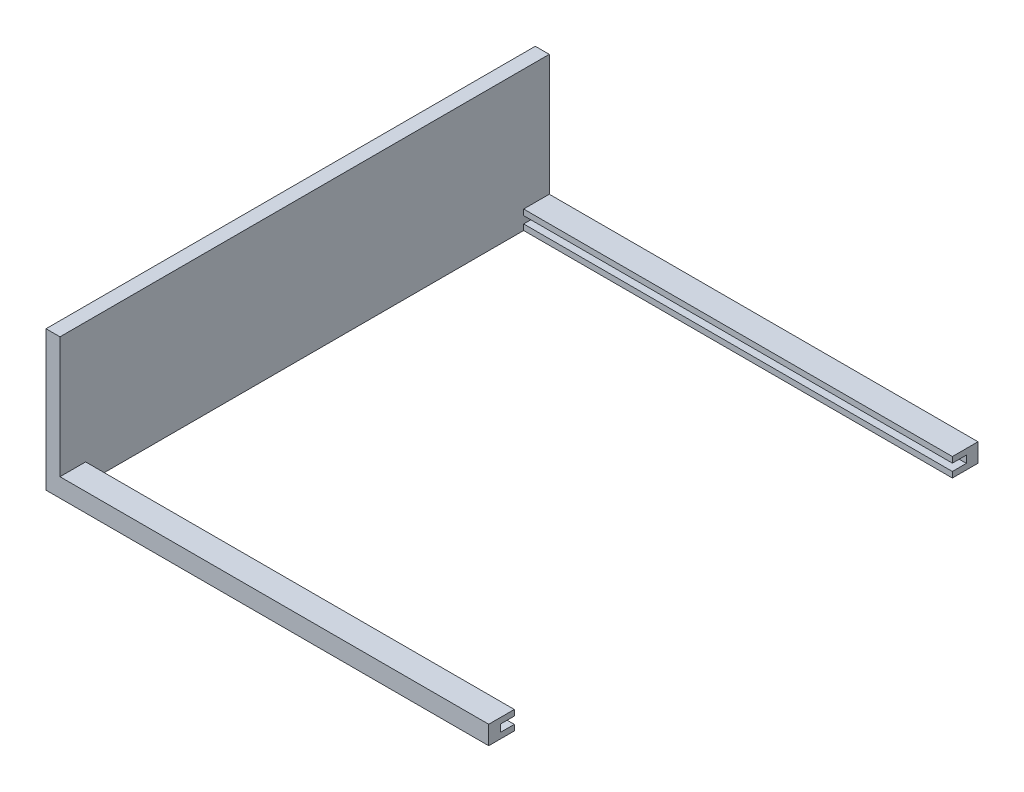
SolidWorks part; units mm, degrees
ref_plane "Front Plane" through (0, 0, 0) normal (0, 0, 1) x (1, 0, 0)
ref_plane "Top Plane" through (0, 0, 0) normal (0, 1, 0) x (1, 0, 0)
ref_plane "Right Plane" through (0, 0, 0) normal (1, 0, 0) x (0, 0, -1)
sketch "Sketch1" plane through (0, 0, 0) normal (0, 0, 1) x (1, 0, 0)
  line L0 (0, 26) -> (0, 0)
  line L1 (0, 26) -> (-3, 26)
  line L2 (-3, 26) -> (-3, -4)
  line L3 (-3, -4) -> (92, -4)
  line L4 (92, -4) -> (92, 0)
  line L5 (92, 0) -> (0, 0)
  dimension "D1" = 95
  dimension "D2" = 4
  dimension "D3" = 3
  dimension "D4" = 30
extrude "Boss-Extrude1" add sketch "Sketch1" against normal blind 105
sketch "Sketch2" plane through (0, 0, 0) normal (1, 0, 0) x (0, 0, -1)
  line L1 (99.5, -1.23) -> (102.5, -1.23)
  line L2 (102.5, -1.23) -> (102.5, -2.77)
  line L6 (5.5, 0) -> (5.5, -1.23)
  line L7 (102.5, -2.77) -> (99.5, -2.77)
  line L8 (105, 0) -> (0, 0) construction
  line L9 (99.5, -1.23) -> (99.5, 0)
  line L15 (105, 0) -> (0, 0) construction
  line L16 (105, -4) -> (0, -4) construction
  line L17 (5.5, -4) -> (99.5, -4)
  line L18 (99.5, -4) -> (99.5, -2.77)
  line L19 (99.5, 0) -> (5.5, 0)
  line L20 (0, -4) -> (0, 0) construction
  line L21 (5.5, -1.23) -> (2.5, -1.23)
  line L22 (2.5, -1.23) -> (2.5, -2.77)
  line L23 (2.5, -2.77) -> (5.5, -2.77)
  line L24 (5.5, -2.77) -> (5.5, -4)
  line L25 (52.5, 26) -> (52.5, 16.3677) construction
  line L26 (105, 26) -> (0, 26) construction
  dimension "D1" = 94
  dimension "D2" = 5.5
  dimension "D3" = 3
  dimension "D4" = 1.54
  dimension "D5" = 1.23
  dimension "D6" = 1.23
  dimension "D7" = 3
extrude "Cut-Extrude1" cut sketch "Sketch2" along normal blind 100
